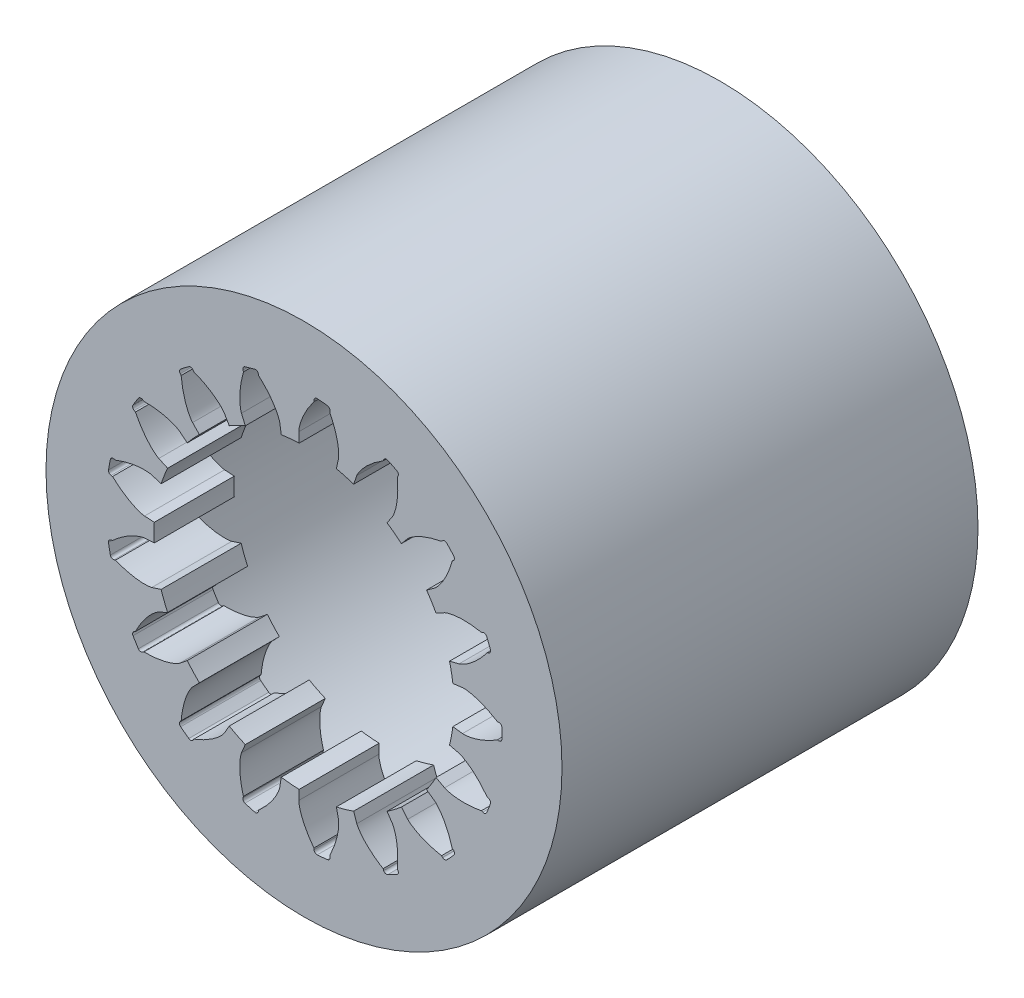
SolidWorks part; units mm, degrees
ref_plane "Front Plane" through (0, 0, 0) normal (0, 0, 1) x (1, 0, 0)
ref_plane "Top Plane" through (0, 0, 0) normal (0, 1, 0) x (1, 0, 0)
ref_plane "Right Plane" through (0, 0, 0) normal (1, 0, 0) x (0, 0, -1)
ref_axis "Gear Axis" through (0, 0, -1.3001) along (0, 0, 1)
sketch "Blank Sketch" plane through (0, 0, 0) normal (0, 0, 1) x (1, 0, 0)
  circle A0 centre (0, 0) radius 16.125
  circle A1 centre (0, 0) radius 9.375
  dimension "Rim" = 32.25
  dimension "Tip" = 18.75
extrude "Blank" add sketch "Blank Sketch" along normal blind 26
sketch "Tooth Space Sketch" plane through (0, 0, 0) normal (0, 0, 1) x (1, 0, 0)
  line L0 (9.9064, 1.2443) -> (8.0617, 1.0126)
  line L1 (9.9064, -1.2443) -> (8.0617, -1.0126)
  line L2 (8.0617, 1.0126) -> (8.0617, -1.0126)
  line L3 (12.0836, 0.4958) -> (12.1758, 0.4996)
  line L4 (12.0836, -0.4958) -> (12.1758, -0.4996)
  circle A0 centre (0, 0) radius 8.125 construction
  arc A1 (12.3709, 0.3171) -> (12.1758, 0.4996) centre (12.1835, 0.3122) ccw
  arc A2 (12.1758, -0.4996) -> (12.3709, -0.3171) centre (12.1835, -0.3122) ccw
  arc A3 (12.3709, -0.3171) -> (12.3709, 0.3171) centre (0, 0) ccw
  spline S0 degree 4 poles (9.9064, 1.2443) (9.9098, 1.2447) (9.9195, 1.2456) (9.9377, 1.2467) (9.9676, 1.2477) (10.0058, 1.2476) (10.0552, 1.2461) (10.1134, 1.2425) (10.1774, 1.2365) (10.247, 1.2278) (10.3164, 1.2173) (10.3856, 1.2051) (10.4544, 1.1914) (10.5377, 1.1729) (10.6373, 1.1482) (10.7533, 1.1155) (10.8845, 1.0741) (11.0174, 1.0272) (11.1477, 0.9773) (11.2786, 0.9224) (11.4047, 0.8662) (11.5347, 0.8034) (11.6543, 0.7432) (11.7872, 0.6709) (11.894, 0.6111) (12.0337, 0.5271) (12.1158, 0.476) (12.2114, 0.4144) (12.2536, 0.3861) (12.2796, 0.3687) knots 0 0 0 0 0 0.005377 0.015084 0.028532 0.04661 0.064855 0.092111 0.119476 0.146842 0.174209 0.201575 0.228941 0.256307 0.307035 0.361767 0.4165 0.471232 0.525964 0.580697 0.635429 0.690161 0.744894 0.799626 0.854358 0.909091 0.954545 1 1 1 1 1 construction
  spline S1 degree 4 poles (9.9064, 1.2443) (9.9098, 1.2447) (9.9195, 1.2456) (9.9377, 1.2467) (9.9676, 1.2477) (10.0058, 1.2476) (10.0552, 1.2461) (10.1134, 1.2425) (10.1774, 1.2365) (10.247, 1.2278) (10.3164, 1.2173) (10.3856, 1.2051) (10.4544, 1.1914) (10.5377, 1.1729) (10.6373, 1.1482) (10.7533, 1.1155) (10.8845, 1.0741) (11.0174, 1.0272) (11.1477, 0.9773) (11.2786, 0.9224) (11.4047, 0.8662) (11.5347, 0.8034) (11.6543, 0.7432) (11.7872, 0.6709) (11.894, 0.6111) (12.0034, 0.5453) (12.0565, 0.5127) (12.0836, 0.4958) knots 0 0 0 0 0 0.005377 0.015084 0.028532 0.04661 0.064855 0.092111 0.119476 0.146842 0.174209 0.201575 0.228941 0.256307 0.307035 0.361767 0.4165 0.471232 0.525964 0.580697 0.635429 0.690161 0.744894 0.799626 0.854358 0.909091 0.909091 0.909091 0.909091 0.909091
  spline S2 degree 4 poles (9.9064, -1.2443) (9.9098, -1.2447) (9.9195, -1.2456) (9.9377, -1.2467) (9.9676, -1.2477) (10.0058, -1.2476) (10.0552, -1.2461) (10.1134, -1.2425) (10.1774, -1.2365) (10.247, -1.2278) (10.3164, -1.2173) (10.3856, -1.2051) (10.4544, -1.1914) (10.5377, -1.1729) (10.6373, -1.1482) (10.7533, -1.1155) (10.8845, -1.0741) (11.0174, -1.0272) (11.1477, -0.9773) (11.2786, -0.9224) (11.4047, -0.8662) (11.5347, -0.8034) (11.6543, -0.7432) (11.7872, -0.6709) (11.894, -0.6111) (12.0337, -0.5271) (12.1158, -0.476) (12.2114, -0.4144) (12.2536, -0.3861) (12.2796, -0.3687) knots 0 0 0 0 0 0.005377 0.015084 0.028532 0.04661 0.064855 0.092111 0.119476 0.146842 0.174209 0.201575 0.228941 0.256307 0.307035 0.361767 0.4165 0.471232 0.525964 0.580697 0.635429 0.690161 0.744894 0.799626 0.854358 0.909091 0.954545 1 1 1 1 1 construction
  spline S3 degree 4 poles (9.9064, -1.2443) (9.9098, -1.2447) (9.9195, -1.2456) (9.9377, -1.2467) (9.9676, -1.2477) (10.0058, -1.2476) (10.0552, -1.2461) (10.1134, -1.2425) (10.1774, -1.2365) (10.247, -1.2278) (10.3164, -1.2173) (10.3856, -1.2051) (10.4544, -1.1914) (10.5377, -1.1729) (10.6373, -1.1482) (10.7533, -1.1155) (10.8845, -1.0741) (11.0174, -1.0272) (11.1477, -0.9773) (11.2786, -0.9224) (11.4047, -0.8662) (11.5347, -0.8034) (11.6543, -0.7432) (11.7872, -0.6709) (11.894, -0.6111) (12.0034, -0.5453) (12.0565, -0.5127) (12.0836, -0.4958) knots 0 0 0 0 0 0.005377 0.015084 0.028532 0.04661 0.064855 0.092111 0.119476 0.146842 0.174209 0.201575 0.228941 0.256307 0.307035 0.361767 0.4165 0.471232 0.525964 0.580697 0.635429 0.690161 0.744894 0.799626 0.854358 0.909091 0.909091 0.909091 0.909091 0.909091
  dimension "Root" = 12.375
  dimension "Fillet" = 0.1875
  dimension "Cap" = 16.25
extrude "Tooth Space" cut sketch "Tooth Space Sketch" against normal through all both and the other way through all both
pattern_circular "Teeth" count 17 over 360 about axis through (0, 0, -1.3001) along (0, 0, 1) of "Tooth Space"
ref_plane "Relief Mid Plane" through (0, 0, 13) normal (0, 0, 1) x (1, 0, 0)
sketch "Relief Sketch" plane through (0, 0, 13) normal (0, 0, 1) x (1, 0, 0)
  circle A0 centre (0, 0) radius 13
extrude "Relief Bore" cut sketch "Relief Sketch" against normal mid plane 16
equation "\"No. of Teeth\"= 17"
equation "\"Module\"= 1.25"
equation "\"Pressure Angle\"= 20"
equation "\"Inner Diameter\"= ( \"No. of Teeth\" - 2 ) * \"Module\""
equation "\"Pitch Diameter\"= \"No. of Teeth\" * \"Module\""
equation "\"Backlash\"= 0.3 * \"Module\""
equation "\"Arc Length\"= ( ( \"Module\" * pi ) / 2 + \"Backlash\" )"
equation "\"Fillet Radius\"= 0.15 * \"Module\""
equation "\"Tooth Depth\"= IIF ( \"Module\" <= 1.25 , \"Module\" * 2.4 , \"Module\" * 2.25 )"
equation "\"Face Width\"= 26"
equation "\"Root Diameter\"= \"Inner Diameter\" + 2 * \"Tooth Depth\""
equation "\"Rim Diameter\"= \"Root Diameter\" + 6 * \"Module\""
equation "\"Base Diameter\"= \"Pitch Diameter\" * cos ( \"Pressure Angle\" )"
equation "\"Base Radius\"= \"Base Diameter\" / 2"
equation "\"Tooth Thickness\"= \"Module\" * pi - \"Arc Length\""
equation "\"Half Space Angle\"= ( \"Arc Length\" / \"Pitch Diameter\" ) * 180 / pi"
equation "\"Involute Fn\"= tan ( \"Pressure Angle\" ) - \"Pressure Angle\" * pi / 180"
equation "\"Flank Offset\"= 0 - \"Arc Length\" / \"Pitch Diameter\" - \"Involute Fn\""
equation "\"Tip Cap Diameter\"= \"Inner Diameter\" - 2 * \"Module\""
equation "\"Flank Start Diameter\"= IIF ( \"Base Diameter\" >= ( \"Inner Diameter\" - \"Module\" ) , \"Base Diameter\" , \"Inner Diameter\" - \"Module\" )"
equation "\"Flank End Diameter\"= \"Root Diameter\" - 3 * \"Fillet Radius\""
equation "\"Involute t1\"= ( abs ( ( \"Flank Start Diameter\" / \"Base Diameter\" ) ^ 2 - 1 ) ) ^ 0.5"
equation "\"Involute t2\"= ( abs ( ( \"Flank End Diameter\" / \"Base Diameter\" ) ^ 2 - 1 ) ) ^ 0.5"
equation "\"Flank Arc Radius\"= ( \"Pitch Diameter\" / 2 ) * sin ( \"Pressure Angle\" )"
equation "\"Flank Centre Angle\"= \"Half Space Angle\" - \"Pressure Angle\""
equation "\"Rim@Blank Sketch\"= \"Rim Diameter\""
equation "\"Tip@Blank Sketch\"= \"Inner Diameter\""
equation "\"Width@Blank\"= \"Face Width\""
equation "\"Root@Tooth Space Sketch\"= \"Root Diameter\" / 2"
equation "\"Fillet@Tooth Space Sketch\"= \"Fillet Radius\""
equation "\"Cap@Tooth Space Sketch\"= \"Tip Cap Diameter\""
equation "\"Count@Teeth\"= \"No. of Teeth\""
